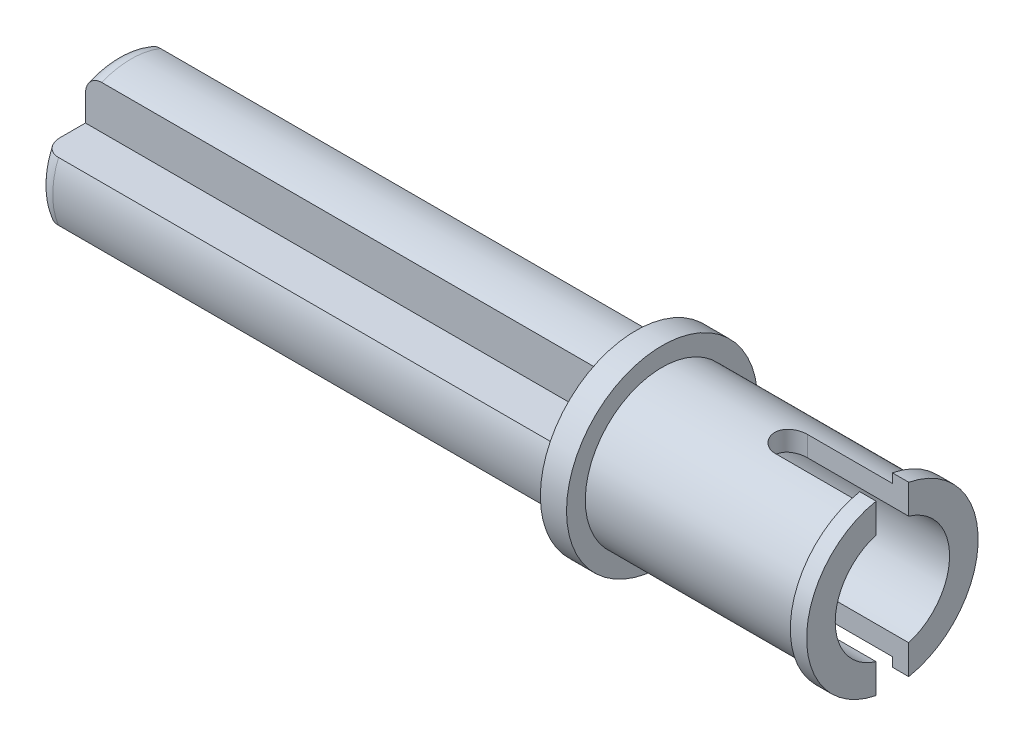
SolidWorks part; units mm, degrees
ref_plane "Front Plane" through (0, 0, 0) normal (0, 0, 1) x (1, 0, 0)
ref_plane "Top Plane" through (0, 0, 0) normal (0, 1, 0) x (1, 0, 0)
ref_plane "Right Plane" through (0, 0, 0) normal (1, 0, 0) x (0, 0, -1)
sketch "Sketch1" plane through (0, 0, 0) normal (1, 0, 0) x (0, 0, -1)
  circle A0 centre (0, 0) radius 1.75
  circle A1 centre (0, 0) radius 2.925
  dimension "D1" = 3.5
  dimension "D2" = 5.85
extrude "Middle Ring" add sketch "Sketch1" along normal blind 0.8
sketch "Sketch2" plane through (0, 0, 0) normal (1, 0, 0) x (0, 0, -1)
  circle A0 centre (0, 0) radius 1.75 construction
  circle A1 centre (0, 0) radius 1.75
  circle A2 centre (0, 0) radius 2.35
  dimension "D1" = 4.7
extrude "Outer Body" add sketch "Sketch2" along normal blind 7.35
sketch "Sketch3" plane through (7.35, 0, 0) normal (1, 0, 0) x (0, 0, -1)
  circle A0 centre (0, 0) radius 1.75 construction
  circle A1 centre (0, 0) radius 1.75
  circle A2 centre (0, 0) radius 2.625
  dimension "D1" = 5.25
extrude "Outer Rim" add sketch "Sketch3" along normal blind 0.5
sketch "Sketch5" plane through (0, 0, 0) normal (0, 1, 0) x (1, 0, 0)
  line L0 (10.95, 0) -> (4.75, 0) construction
  line L1 (7.85, -2.625) -> (7.85, 2.625) construction
  line L2 (10.95, -0.5) -> (4.75, -0.5)
  line L3 (10.95, 0.5) -> (4.75, 0.5)
  line L4 (0, 0) -> (0, 3.8777) construction
  line L5 (-10.95, 0) -> (-4.75, 0) construction
  line L6 (-10.95, -0.5) -> (-4.75, -0.5)
  line L7 (-10.95, 0.5) -> (-4.75, 0.5)
  arc A0 (10.95, -0.5) -> (10.95, 0.5) centre (10.95, 0) ccw
  arc A1 (4.75, 0.5) -> (4.75, -0.5) centre (4.75, 0) ccw
  arc A2 (-10.95, -0.5) -> (-10.95, 0.5) centre (-10.95, 0) cw
  arc A3 (-4.75, 0.5) -> (-4.75, -0.5) centre (-4.75, 0) cw
  point P5 (7.85, 0)
  point P14 (-7.85, 0)
  dimension "D2" = 8.5
  dimension "D1" = 1
  dimension "D3" = 3.6
extrude "Side Slots" cut sketch "Sketch5" against normal through all both and the other way through all
sketch "Sketch6" plane through (0, 0, 0) normal (-1, 0, 0) x (0, 0, 1)
  line L1 (0.9, -2.4) -> (-0.9, -2.4)
  line L2 (0.9, -2.4) -> (0.9, 2.4)
  line L3 (0.9, 2.4) -> (-0.9, 2.4)
  line L4 (-0.9, -2.4) -> (-0.9, 2.4)
  line L5 (0.9, -2.4) -> (-0.9, 2.4) construction
  line L6 (0.9, 2.4) -> (-0.9, -2.4) construction
  line L7 (2.4, -0.9) -> (-2.4, -0.9)
  line L8 (2.4, -0.9) -> (2.4, 0.9)
  line L9 (2.4, 0.9) -> (-2.4, 0.9)
  line L10 (-2.4, -0.9) -> (-2.4, 0.9)
  line L11 (2.4, -0.9) -> (-2.4, 0.9) construction
  line L12 (2.4, 0.9) -> (-2.4, -0.9) construction
  circle A0 centre (0, 0) radius 2.4
  circle M10 centre (0, 0) radius 1.75
  dimension "D1" = 4.8
  dimension "D2" = 1.8
extrude "Axle" add sketch "Sketch6" along normal offset from surface (15.95 mm away) 23.8 contours L2 L9 L4 L7 | L4 L9 L7 M10 | L9 L2 L4 M10 | L9 A0 L7 M10 | L2 A0 L4 M10 | A0 L9 L7 M10 | L9 L2 L7 M10 | L2 L7 L4 M10 | L4 A0 L2 M10 up to face at (7.85, 0, -1.3437)
fillet "Fillet1" radius 0.5 4 edges at (-15.95, 0, 2.4) (-15.95, 0, -2.4) (-15.95, 2.4, 0) (-15.95, -2.4, 0)
sketch "Sketch7" plane through (0, 0, 0) normal (-1, 0, 0) x (0, 0, 1)
  circle A0 centre (0, 0) radius 2.925 construction
  circle A1 centre (0, 0) radius 2.925
extrude "Axle Base" add sketch "Sketch7" against normal blind 0.8
